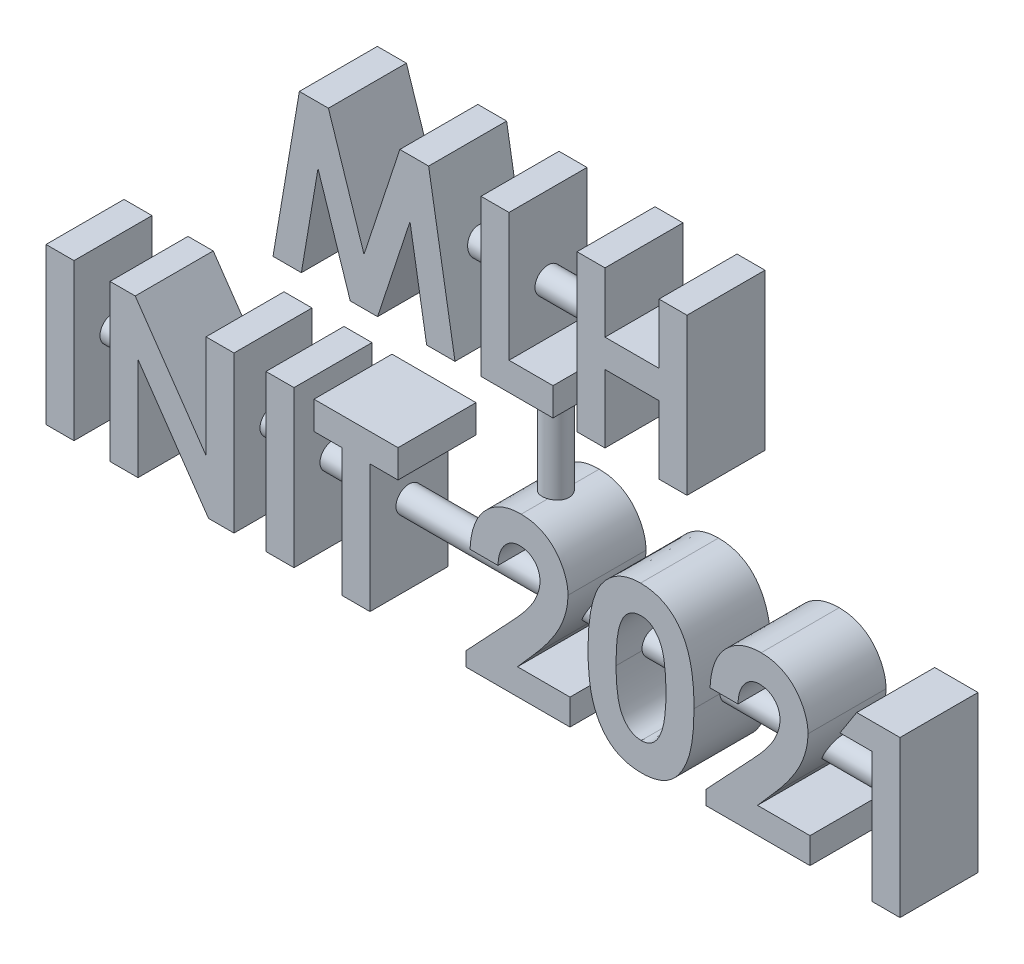
SolidWorks part; units mm, degrees
ref_plane "Front Plane" through (0, 0, 0) normal (0, 0, 1) x (1, 0, 0)
ref_plane "Top Plane" through (0, 0, 0) normal (0, 1, 0) x (1, 0, 0)
ref_plane "Right Plane" through (0, 0, 0) normal (1, 0, 0) x (0, 0, -1)
sketch "Sketch1" plane through (0, 0, 0) normal (0, 0, 1) x (1, 0, 0)
  line L0 (0, 0) -> (-100, 0) construction
  line L1 (-100, 0) -> (100, 0) construction
  text T0 "MLH\r\nINIT 2021" font "Century Gothic" height 30
  dimension "D1" = 100
  dimension "D2" = 100
extrude "Boss-Extrude1" add sketch "Sketch1" along normal blind 15
sketch "Sketch2" plane through (38.4615, 0, 0) normal (1, 0, 0) x (0, 0, -1)
  line L0 (0, 30) -> (-15, 0) construction
  circle A0 centre (-7.5, 15) radius 2.5
  dimension "D1" = 5
extrude "Boss-Extrude2" add sketch "Sketch2" against normal up to body separate body
sketch "Sketch4" plane through (79.4231, 0, 0) normal (1, 0, 0) x (0, 0, -1)
  line L0 (0, -19.8462) -> (-15, -49.8462) construction
  line L1 (-15, -19.8462) -> (-15, -49.8462) construction
  line L2 (-15, -49.8462) -> (0, -49.8462) construction
  circle A0 centre (-7.5, -34.8462) radius 2.5
  dimension "D1" = 5
extrude "Boss-Extrude3" add sketch "Sketch4" against normal up to body separate body
sketch "Sketch5" plane through (0, 0, 0) normal (0, -1, 0) x (1, 0, 0)
  line L0 (-1.1538, 0) -> (12.6923, 15) construction
  circle A0 centre (5.7692, 7.5) radius 2.5
  dimension "D1" = 5
extrude "Boss-Extrude4" add sketch "Sketch5" along normal up to body separate body
